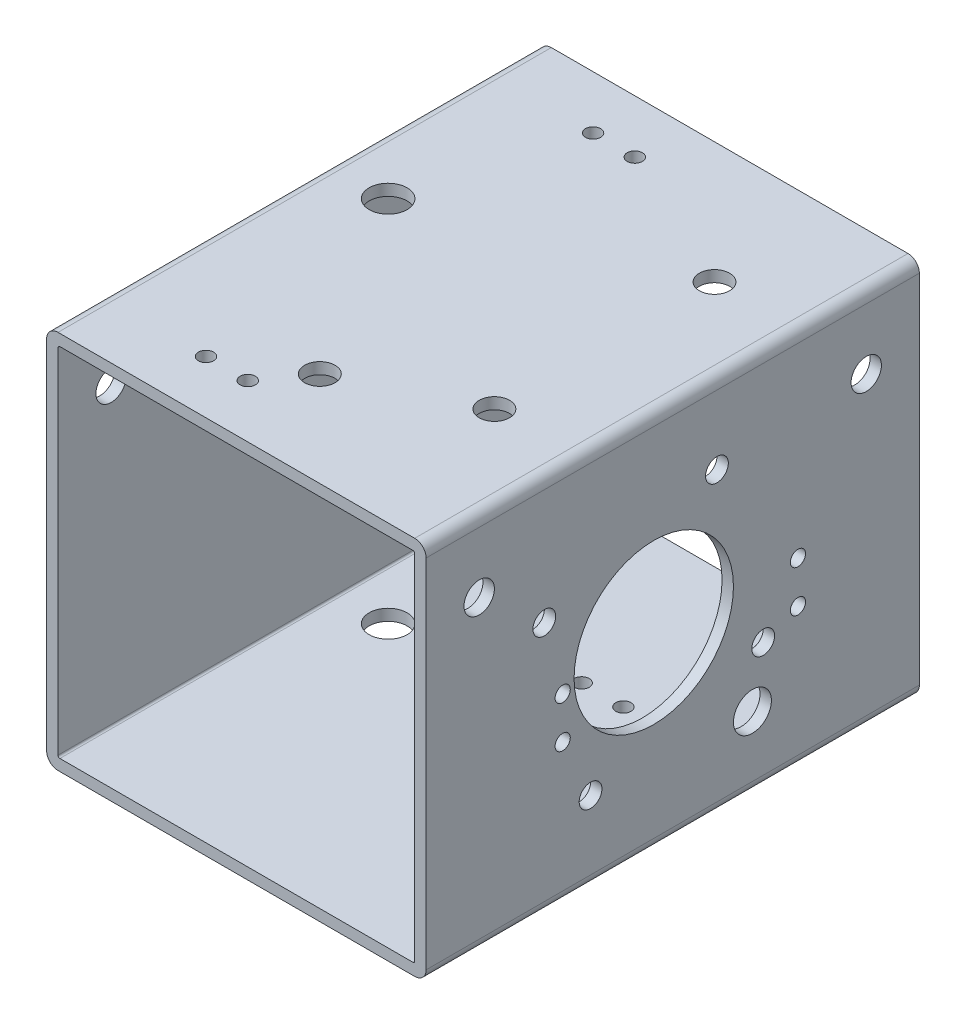
SolidWorks part; units mm, degrees
ref_plane "Front Plane" through (0, 0, 0) normal (0, 0, 1) x (1, 0, 0)
ref_plane "Top Plane" through (0, 0, 0) normal (0, 1, 0) x (1, 0, 0)
ref_plane "Right Plane" through (0, 0, 0) normal (1, 0, 0) x (0, 0, -1)
sketch "Sketch1" plane through (0, 0, 0) normal (0, 0, 1) x (1, 0, 0)
  line L1 (-50, 50) -> (50, 50)
  line L2 (-50, 50) -> (-50, -50)
  line L3 (-50, -50) -> (50, -50)
  line L4 (50, 50) -> (50, -50)
  line L5 (-50, 50) -> (50, -50) construction
  line L6 (-50, -50) -> (50, 50) construction
  point P0 (0, 0)
  dimension "D1" = 100
  dimension "D2" = 100
extrude "Extrude-Thin1" add sketch "Sketch1" along normal blind 130 thin
fillet "Fillet1" radius 0.5 4 edges at (-47, -47, 65) (-47, 47, 65) (47, 47, 65) (47, -47, 65)
fillet "Fillet2" radius 3 4 edges at (50, -50, 65) (-50, -50, 65) (50, 50, 65) (-50, 50, 65)
sketch "Holes - top" plane through (0, 0, 0) normal (0, 1, 0) x (1, 0, 0)
  line L0 (-3, 0) -> (-3, -130) construction
  line L1 (47, -130) -> (-47, -130) construction
  line L2 (-23, 0) -> (-23, -130) construction
  line L3 (47, 0) -> (-47, 0) construction
  line L4 (17, 0) -> (17, -130) construction
  circle A0 centre (-34, -56) radius 11 construction
  circle A1 centre (28, -90) radius 11 construction
  circle A2 centre (28, -32) radius 11 construction
  dimension "D4" = 22
  dimension "D1" = 40
  dimension "D2" = 40
  dimension "D3" = 32
  dimension "D5" = 56
  dimension "D6" = 3
hole_wizard "Ø8.0 (8) Diameter Hole2" positions "Sketch6" profile "Sketch5" hole size "Ø8.0" standard "ANSI Metric" end condition through all
sketch "Sketch6" plane through (0, 50, 0) normal (0, 1, 0) x (1, 0, 0)
  point P0 (28, -32)
  point P6 (28, -90)
sketch "Sketch5" plane through (28, 50, 32) normal (1, 0, 0) x (0, 0, 1)
  line L0 (0, 0) -> (0, 100)
  line L1 (0, 100) -> (4, 100)
  line L2 (4, 100) -> (4, 0)
  line L5 (4, 0) -> (0, 0)
  line L11 (0, -6.35) -> (0, 107.95) construction
  dimension "Thru Hole Dia." = 8
  dimension "Thru Hole Depth" = 100
sketch "Holes - side" plane through (0, 0, 0) normal (1, 0, 0) x (0, 0, -1)
  line L0 (0, 0) -> (-130, 0) construction
  line L1 (-130, -47) -> (-130, 47) construction
  line L2 (-130, 20) -> (0, 20) construction
  line L3 (0, -47) -> (0, 47) construction
  line L4 (-130, -20) -> (0, -20) construction
  circle A0 centre (-116, 31) radius 11 construction
  circle A1 centre (-14, 31) radius 11 construction
  circle A2 centre (-44, -31) radius 11 construction
  dimension "D1" = 40
  dimension "D2" = 22
  dimension "D3" = 14
  dimension "D4" = 14
  dimension "D5" = 44
hole_wizard "Ø8.0 (8) Diameter Hole3" positions "Sketch9" profile "Sketch8" hole size "Ø8.0" standard "ANSI Metric" end condition through all
sketch "Sketch9" plane through (50, 0, 0) normal (1, 0, 0) x (0, 0, -1)
  point P0 (-14, 31)
  point P3 (-116, 31)
sketch "Sketch8" plane through (50, 31, 14) normal (0, 1, 0) x (0, 0, -1)
  line L0 (0, 0) -> (0, 100)
  line L1 (0, 100) -> (4, 100)
  line L2 (4, 100) -> (4, 0)
  line L5 (4, 0) -> (0, 0)
  line L11 (0, -6.35) -> (0, 107.95) construction
  dimension "Thru Hole Dia." = 8
  dimension "Thru Hole Depth" = 100
hole_wizard "Ø10.0 (10) Diameter Hole1" positions "Sketch12" profile "Sketch11" hole size "Ø10.0" standard "ANSI Metric" end condition through all
sketch "Sketch12" plane through (0, 50, 0) normal (0, 1, 0) x (1, 0, 0)
  point P0 (-34, -56)
sketch "Sketch11" plane through (-34, 50, 56) normal (1, 0, 0) x (0, 0, 1)
  line L0 (0, 0) -> (0, 100)
  line L1 (0, 100) -> (5, 100)
  line L2 (5, 100) -> (5, 0)
  line L5 (5, 0) -> (0, 0)
  line L11 (0, -6.35) -> (0, 107.95) construction
  dimension "Thru Hole Dia." = 10
  dimension "Thru Hole Depth" = 100
hole_wizard "Ø10.0 (10) Diameter Hole2" positions "Sketch14" profile "Sketch13" hole size "Ø10.0" standard "ANSI Metric" end condition through all
sketch "Sketch14" plane through (50, 0, 0) normal (1, 0, 0) x (0, 0, -1)
  point P0 (-44, -31)
sketch "Sketch13" plane through (50, -31, 44) normal (0, 1, 0) x (0, 0, -1)
  line L0 (0, 0) -> (0, 100)
  line L1 (0, 100) -> (5, 100)
  line L2 (5, 100) -> (5, 0)
  line L5 (5, 0) -> (0, 0)
  line L11 (0, -6.35) -> (0, 107.95) construction
  dimension "Thru Hole Dia." = 10
  dimension "Thru Hole Depth" = 100
sketch "Holes - Nema 23 motor" plane through (0, 0, 0) normal (1, 0, 0) x (0, 0, -1)
  line L0 (-98.8427, 16.6524) -> (-53.3476, 28.8427) construction
  line L1 (-98.8427, 16.6524) -> (-86.6524, -28.8427) construction
  line L2 (-53.3476, 28.8427) -> (-41.1573, -16.6524) construction
  line L3 (-86.6524, -28.8427) -> (-41.1573, -16.6524) construction
  line L4 (-98.8427, 16.6524) -> (-41.1573, -16.6524) construction
  line L5 (-53.3476, 28.8427) -> (-86.6524, -28.8427) construction
  line L6 (0, 0) -> (-130, 0) construction
  point P1 (-70, 0)
  dimension "D1" = 70
  dimension "D2" = 47.1
  dimension "D3" = 47.1
  dimension "D4" = 15
hole_wizard "Ø21.0 (21) Diameter Hole1" positions "Sketch24" profile "Sketch23" hole size "Ø21.0" standard "ANSI Metric"
sketch "Sketch24" plane through (50, 0, 0) normal (1, 0, 0) x (0, 0, -1)
  point P0 (-70, 0)
sketch "Sketch23" plane through (50, 0, 70) normal (0, 1, 0) x (0, 0, -1)
  line L0 (0, 0) -> (0, 3)
  line L1 (0, 3) -> (21, 3)
  line L2 (21, 3) -> (21, 0)
  line L5 (21, 0) -> (0, 0)
  line L11 (0, -6.35) -> (0, 107.95) construction
  dimension "Thru Hole Dia." = 42
  dimension "Thru Hole Depth" = 3
hole_wizard "Ø6.0 (6) Diameter Hole1" positions "Sketch26" profile "Sketch25" hole size "Ø6.0" standard "ANSI Metric"
sketch "Sketch26" plane through (50, 0, 0) normal (1, 0, 0) x (0, 0, -1)
  point P0 (-41.1573, -16.6524)
  point P3 (-53.3476, 28.8427)
  point P6 (-98.8427, 16.6524)
  point P9 (-86.6524, -28.8427)
sketch "Sketch25" plane through (50, -16.6524, 41.1573) normal (0, 1, 0) x (0, 0, -1)
  line L0 (0, 0) -> (0, 3)
  line L1 (0, 3) -> (3, 3)
  line L2 (3, 3) -> (3, 0)
  line L5 (3, 0) -> (0, 0)
  line L11 (0, -6.35) -> (0, 107.95) construction
  dimension "Thru Hole Dia." = 6
  dimension "Thru Hole Depth" = 3
sketch "Sketch33" plane through (0, 50, 0) normal (0, 1, 0) x (1, 0, 0)
  line L0 (47, -130) -> (-47, -130) construction
  line L1 (-50, -130) -> (-50, 0) construction
  circle A0 centre (-3, -105) radius 4
  dimension "D3" = 8
  dimension "D2" = 47
  dimension "D1" = 25
extrude "Cut-Extrude1" cut sketch "Sketch33" against normal blind 10
sketch "Sketch34" plane through (0, 50, 0) normal (0, 1, 0) x (1, 0, 0)
  line L0 (-50, -130) -> (-50, 0) construction
  line L1 (47, 0) -> (-47, 0) construction
  line L2 (-64.0721, -65) -> (-167.4631, -65) construction
  circle A0 centre (-22, -14) radius 2
  circle A1 centre (-11, -14) radius 2
  circle A2 centre (-11, -116) radius 2
  circle A3 centre (-22, -116) radius 2
  dimension "D1" = 4
  dimension "D2" = 28
  dimension "D3" = 14
  dimension "D4" = 11
  dimension "D5" = 65
extrude "Cut-Extrude2" cut sketch "Sketch34" against normal blind 10
sketch "Sketch35" plane through (-50, 0, 0) normal (-1, 0, 0) x (0, 0, 1)
  line L0 (0, 50) -> (130, 50) construction
  line L2 (0, 47) -> (0, -47) construction
  circle A0 centre (56, 19) radius 2
  circle A1 centre (56, 8) radius 2
  dimension "D1" = 4
  dimension "D2" = 31
  dimension "D3" = 56
  dimension "D4" = 11
extrude "Cut-Extrude3" cut sketch "Sketch35" against normal blind 10
sketch "Sketch36" plane through (0, -50, 0) normal (0, -1, 0) x (1, 0, 0)
  line L0 (-47, 0) -> (47, 0) construction
  line L1 (50, 130) -> (50, 0) construction
  circle A0 centre (16, 44) radius 2
  circle A1 centre (5, 44) radius 2
  dimension "D1" = 4
  dimension "D2" = 44
  dimension "D3" = 34
  dimension "D4" = 11
extrude "Cut-Extrude4" cut sketch "Sketch36" against normal blind 10
sketch "Sketch37" plane through (50, 0, 0) normal (1, 0, 0) x (0, 0, -1)
  line L1 (-130, -47) -> (-130, 47) construction
  line L2 (0, -50) -> (-130, -50) construction
  circle A0 centre (-32, -13) radius 2
  circle A1 centre (-32, -2) radius 2
  circle A2 centre (-94, -13) radius 2
  circle A3 centre (-94, -2) radius 2
  dimension "D1" = 98
  dimension "D2" = 37
  dimension "D3" = 4
  dimension "D4" = 11
  dimension "D5" = 36
extrude "Cut-Extrude5" cut sketch "Sketch37" against normal blind 10
sketch "Sketch38" plane through (-50, 0, 0) normal (-1, 0, 0) x (0, 0, 1)
  line L0 (0, 50) -> (130, 50) construction
  line L1 (0, 47) -> (0, -47) construction
  circle A0 centre (56, 35) radius 3.1
  circle A1 centre (56, -15) radius 3.1
  dimension "D1" = 6.2
  dimension "D2" = 15
  dimension "D3" = 65
  dimension "D4" = 56
extrude "Cut-Extrude6" cut sketch "Sketch38" against normal up to next
sketch "Sketch39" plane through (0, -50, 0) normal (0, -1, 0) x (1, 0, 0)
  line L0 (50, 130) -> (50, 0) construction
  line L1 (-47, 0) -> (47, 0) construction
  circle A0 centre (-20, 44) radius 3.1
  circle A1 centre (38, 44) radius 3.1
  dimension "D1" = 6.2
  dimension "D2" = 12
  dimension "D3" = 70
  dimension "D4" = 44
extrude "Cut-Extrude7" cut sketch "Sketch39" against normal up to next
equation "\"a\"= \"Trolley Profile@Plasma Beta.Assembly\""
equation "\"b\"= \"Trolley Profile Thickness@Plasma Beta.Assembly\""
equation "\"L\"= 130"
equation "\"D2@Sketch1\"=\"a\""
equation "\"D1@Sketch1\"=\"a\""
equation "\"D1@Extrude-Thin1\"=\"L\""
equation "\"D5@Extrude-Thin1\"=\"b\""
equation "\"D1@Fillet2\"=\"b\""
equation "\"d-bearing\"= 22'diameter of bearing"
equation "\"a-small\"= \"Beam Profile@Plasma Beta.Assembly\"'profile of smaller beam"
equation "\"D4@Holes - top\"=\"d-bearing\""
equation "\"D2@Holes - side\"=\"d-bearing\""
equation "\"D1@Holes - top\"=\"a-small\""
equation "\"D1@Holes - side\"=\"a-small\""
